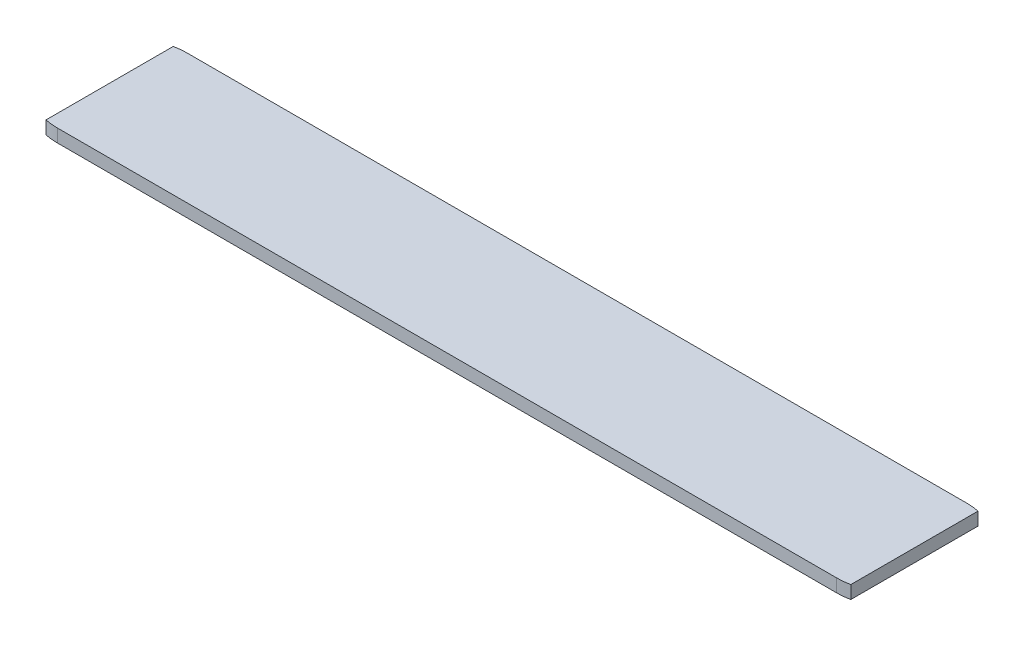
SolidWorks part; units mm, degrees
ref_plane "Front Plane" through (0, 0, 0) normal (0, 0, 1) x (1, 0, 0)
ref_plane "Top Plane" through (0, 0, 0) normal (0, 1, 0) x (1, 0, 0)
ref_plane "Right Plane" through (0, 0, 0) normal (1, 0, 0) x (0, 0, -1)
sketch "Sketch1" plane through (0, 0, 0) normal (0, 1, 0) x (1, 0, 0)
  line L0 (-47.625, 0) -> (47.625, 0) construction
  line L1 (-47.625, 7.9375) -> (47.625, 7.9375)
  line L2 (-47.625, -7.9375) -> (47.625, -7.9375)
  arc A0 (-47.625, 7.9375) -> (-47.625, -7.9375) centre (-47.625, 0) ccw
  arc A1 (47.625, -7.9375) -> (47.625, 7.9375) centre (47.625, 0) ccw
  point P3 (0, 0)
  dimension "D1" = 7.9375
  dimension "D2" = 95.25
extrude "Boss-Extrude1" add sketch "Sketch1" along normal blind 1.5875
sketch "Sketch2" plane through (0, 1.5875, 0) normal (0, 1, 0) x (1, 0, 0)
  line L1 (-49.2125, 7.9375) -> (49.2125, 7.9375)
  line L2 (-49.2125, 7.9375) -> (-49.2125, -7.9375)
  line L3 (-49.2125, -7.9375) -> (49.2125, -7.9375)
  line L4 (49.2125, 7.9375) -> (49.2125, -7.9375)
  line L5 (-64.4367, 17.9327) -> (67.3799, 17.9327)
  line L6 (-64.4367, 17.9327) -> (-64.4367, -18.648)
  line L7 (-64.4367, -18.648) -> (67.3799, -18.648)
  line L8 (67.3799, 17.9327) -> (67.3799, -18.648)
  dimension "D1" = 98.425
  dimension "D2" = 49.2125
  dimension "D3" = 15.875
  dimension "D4" = 7.9375
extrude "Cut-Extrude1" cut sketch "Sketch2" against normal blind 2.54
